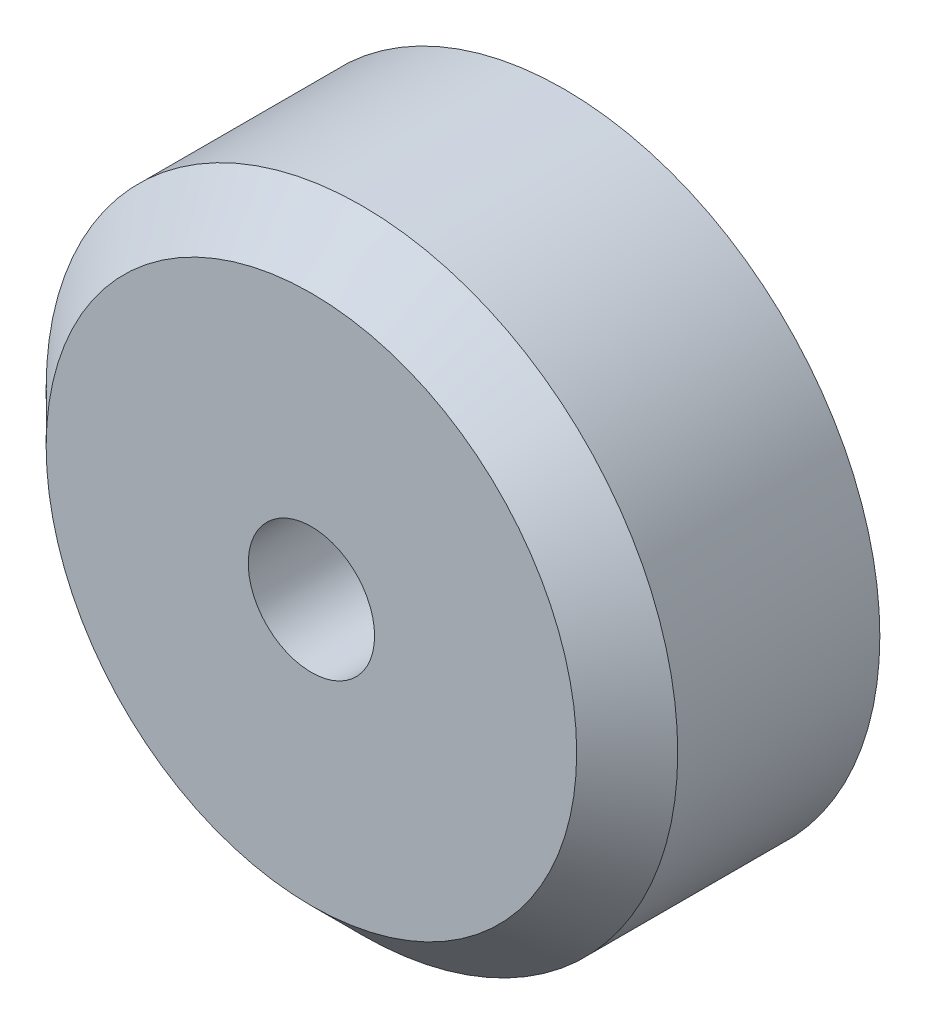
SolidWorks part; units mm, degrees
ref_plane "Front Plane" through (0, 0, 0) normal (0, 0, 1) x (1, 0, 0)
ref_plane "Top Plane" through (0, 0, 0) normal (0, 1, 0) x (1, 0, 0)
ref_plane "Right Plane" through (0, 0, 0) normal (1, 0, 0) x (0, 0, -1)
sketch "Sketch1" plane through (0, 0, 0) normal (0, 0, 1) x (1, 0, 0)
  circle A0 centre (0, 0) radius 1.25
  dimension "D1" = 2.5
extrude "Boss-Extrude1" add sketch "Sketch1" along normal blind 1
sketch "Sketch2" plane through (0, 0, 1) normal (0, 0, 1) x (1, 0, 0)
  circle A0 centre (0, 0) radius 0.25
  dimension "D1" = 0.5
extrude "Cut-Extrude1" cut sketch "Sketch2" against normal through all
chamfer "Chamfer1" distance 0.2 angle 45 1 edges at (1.25, 0, 1)
